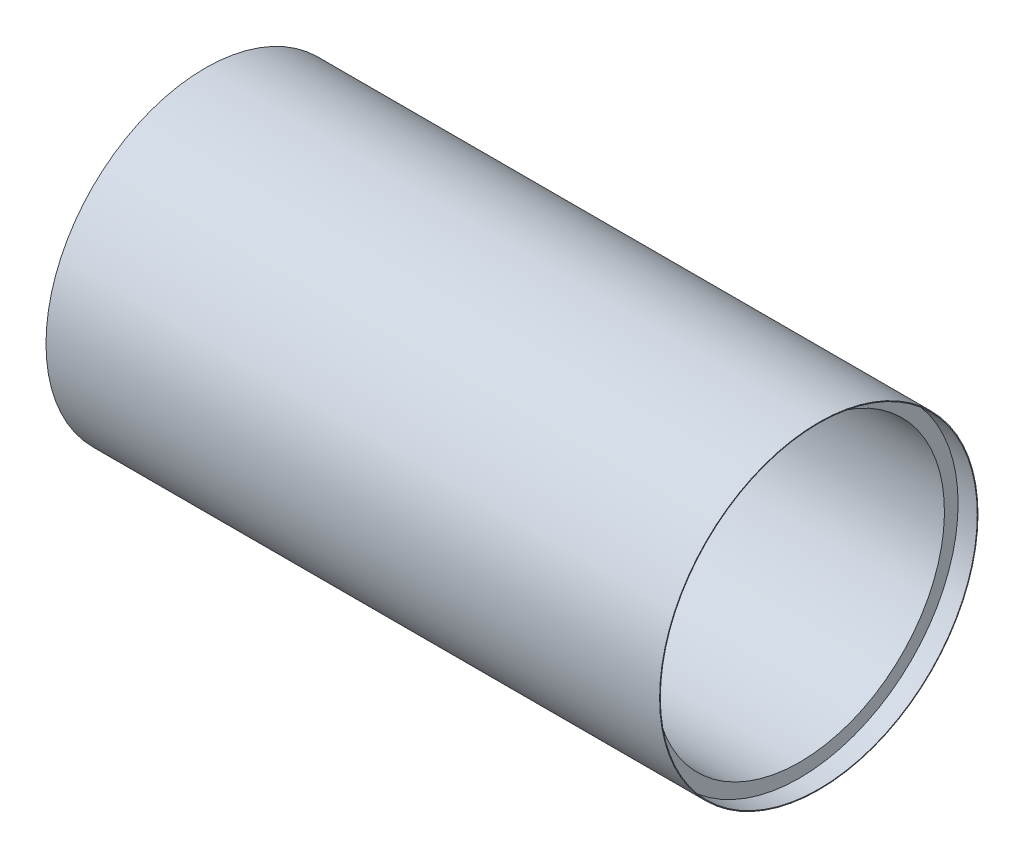
SolidWorks part; units mm, degrees
material "Carbon sandwich"
ref_plane "Front" through (0, 0, 0) normal (0, 0, 1) x (1, 0, 0)
ref_plane "Top" through (0, 0, 0) normal (0, 1, 0) x (1, 0, 0)
ref_plane "Right" through (0, 0, 0) normal (1, 0, 0) x (0, 0, -1)
sketch "Sketch1" plane through (0, 0, 0) normal (0, 0, 1) x (1, 0, 0)
  line L0 (39.1463, 83.9724) -> (49.3063, 83.9724)
  line L1 (49.3063, 83.9724) -> (49.3063, 76.7334)
  line L2 (49.3063, 76.7334) -> (354.1063, 76.7334)
  line L3 (354.1063, 76.7334) -> (354.1063, 83.9724)
  line L4 (354.1063, 83.9724) -> (364.2663, 83.9724)
  line L5 (364.2663, 83.9724) -> (364.2663, 84.3534)
  line L6 (364.2663, 84.3534) -> (39.1463, 84.3534)
  line L7 (39.1463, 84.3534) -> (39.1463, 83.9724)
  line L8 (0, 0) -> (134.0356, 0) construction
  dimension "D1" = 76.7334
  dimension "D2" = 0.381
  dimension "D3" = 10.16
  dimension "D4" = 10.16
  dimension "D5" = 304.8
  dimension "D6" = 84.3534
  dimension "D7" = 0.381
revolve "Revolve1" add sketch "Sketch1" angle 360 about L8
